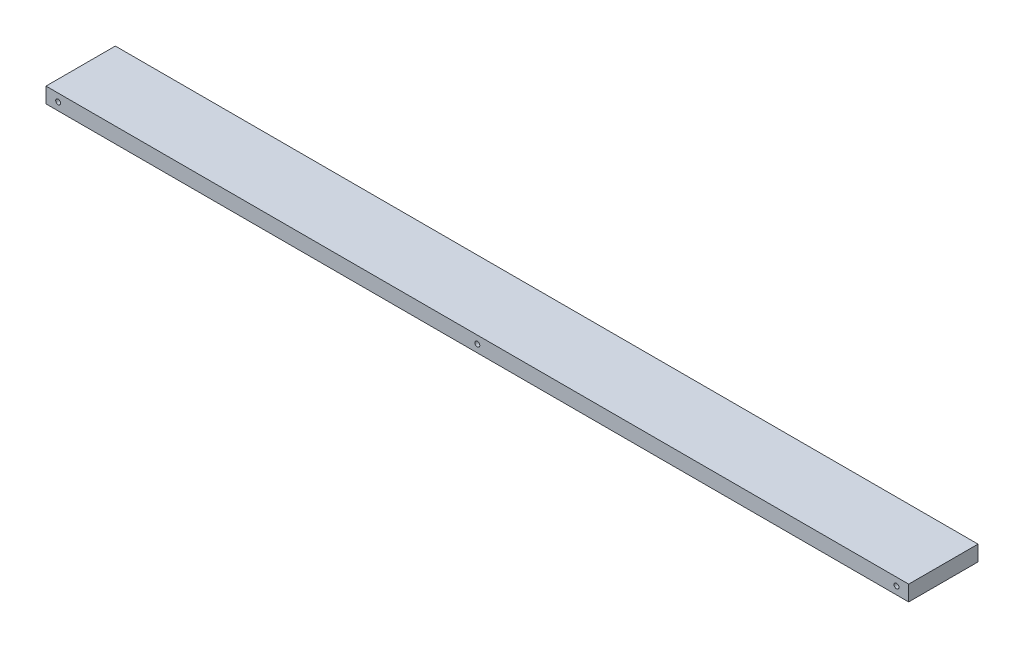
SolidWorks part; units mm, degrees
material "PE High Density Film"
ref_plane "Front Plane" through (0, 0, 0) normal (0, 0, 1) x (1, 0, 0)
ref_plane "Top Plane" through (0, 0, 0) normal (0, 1, 0) x (1, 0, 0)
ref_plane "Right Plane" through (0, 0, 0) normal (1, 0, 0) x (0, 0, -1)
sketch "Sketch1" plane through (0, 0, 0) normal (0, 1, 0) x (1, 0, 0)
  line L1 (0, 0) -> (709, 0)
  line L2 (0, 0) -> (0, 56.98)
  line L3 (0, 56.98) -> (709, 56.98)
  line L4 (709, 0) -> (709, 56.98)
  dimension "D1" = 56.98
  dimension "D2" = 709
extrude "Boss-Extrude1" add sketch "Sketch1" along normal blind 12.7
sketch "Sketch2" plane through (0, 0, 0) normal (0, 0, 1) x (1, 0, 0)
  line L0 (0, 6.35) -> (709, 6.35) construction
  line L1 (0, 12.7) -> (0, 0) construction
  line L2 (709, 12.7) -> (709, 0) construction
  circle A0 centre (699, 6.35) radius 2.0195
  circle A1 centre (354.5, 6.35) radius 2.0195
  circle A2 centre (10, 6.35) radius 2.0195
  dimension "D1" = 4.039
  dimension "D2" = 4.039
  dimension "D3" = 4.039
  dimension "D4" = 344.5
  dimension "D5" = 344.5
  dimension "D6" = 10
extrude "Cut-Extrude1" cut sketch "Sketch2" against normal blind 12.7
